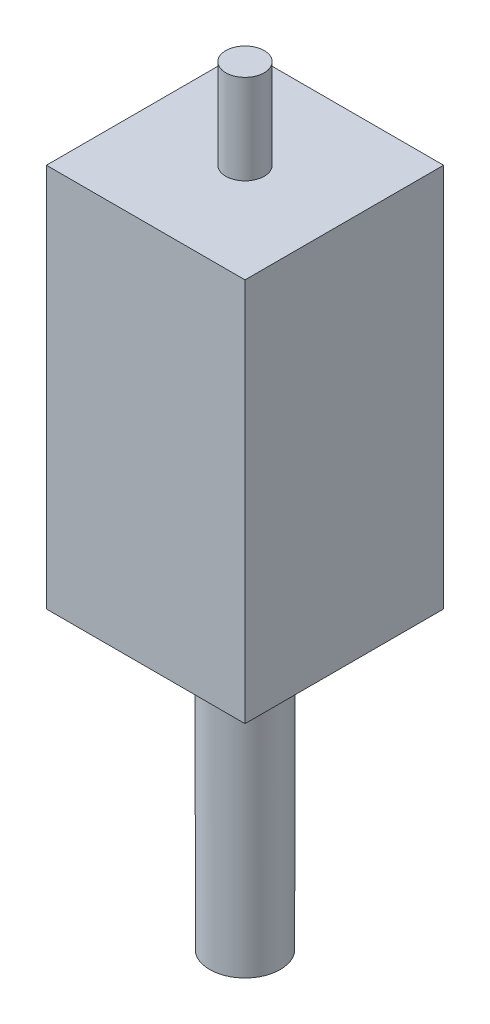
SolidWorks part; units mm, degrees
ref_plane "Front" through (0, 0, 0) normal (0, 0, 1) x (1, 0, 0)
ref_plane "Top" through (0, 0, 0) normal (0, 1, 0) x (1, 0, 0)
ref_plane "Right" through (0, 0, 0) normal (1, 0, 0) x (0, 0, -1)
sketch "Esboço2" plane through (0, 0, 0) normal (0, 0, 1) x (1, 0, 0)
  line L0 (6.8703, 15.805) -> (6.8703, -14.195) construction
  line L1 (-0.8797, 15.805) -> (14.6203, 15.805)
  line L2 (-0.8797, 15.805) -> (-0.8797, -14.195)
  line L3 (-0.8797, -14.195) -> (14.6203, -14.195)
  line L4 (14.6203, 15.805) -> (14.6203, -14.195)
  line L5 (6.8703, -14.195) -> (6.8703, -37.195) construction
  line L6 (6.8703, 15.805) -> (6.8703, 22.805) construction
  dimension "D1" = 15.5
  dimension "D2" = 30
extrude "Ressalto-extrusão1" add sketch "Esboço2" along normal blind 15.5
sketch "Esboço3" plane through (0, 15.805, 0) normal (0, 1, 0) x (1, 0, 0)
  line L0 (14.6203, 0) -> (-0.8797, -15.5) construction
  circle A0 centre (6.8703, -7.75) radius 1.5
extrude "Ressalto-extrusão2" add sketch "Esboço3" along normal blind 7
sketch "Esboço4" plane through (0, -14.195, 0) normal (0, -1, 0) x (1, 0, 0)
  line L0 (14.6203, 15.5) -> (-0.8797, 0) construction
  circle A0 centre (6.8703, 7.75) radius 2.75
extrude "Ressalto-extrusão3" add sketch "Esboço4" along normal blind 23
sketch "Esboço7" plane through (-0.8797, 0, 0) normal (-1, 0, 0) x (0, 0, 1)
  line L0 (7.75, 15.805) -> (7.75, -14.195) construction
  line L1 (15.5, 15.805) -> (0, 15.805) construction
  line L2 (15.5, -14.195) -> (0, -14.195) construction
  line L3 (7.75, -6.695) -> (7.75, 8.305)
  point P9 (7.75, 0.805)
  dimension "D1" = 15
hole_wizard "Broca de rosquear para tarraxa de M31" positions "3DSketch1" profile "Esboço8" hole size "M3" standard "ISO"
sketch3d "3DSketch1"
  point P0 (-0.8797, 8.305, 7.75)
  point P3 (-0.8797, -6.695, 7.75)
sketch "Esboço8" plane through (-0.8797, 8.305, 7.75) normal (0, 1, 0) x (0, 0, 1)
  line L0 (0, 0) -> (0, 1.8511)
  line L1 (0, 1.8511) -> (1.25, 1.1)
  line L2 (1.25, 1.1) -> (1.25, 0)
  line L5 (1.25, 0) -> (0, 0)
  line L10 (0, 1.8511) -> (-1.25, 1.1) construction
  line L11 (0, -6.35) -> (0, 107.95) construction
  dimension "Hole Dia." = 2.5
  dimension "Hole Depth" = 1.1
  dimension "Drill Angle" = 118
